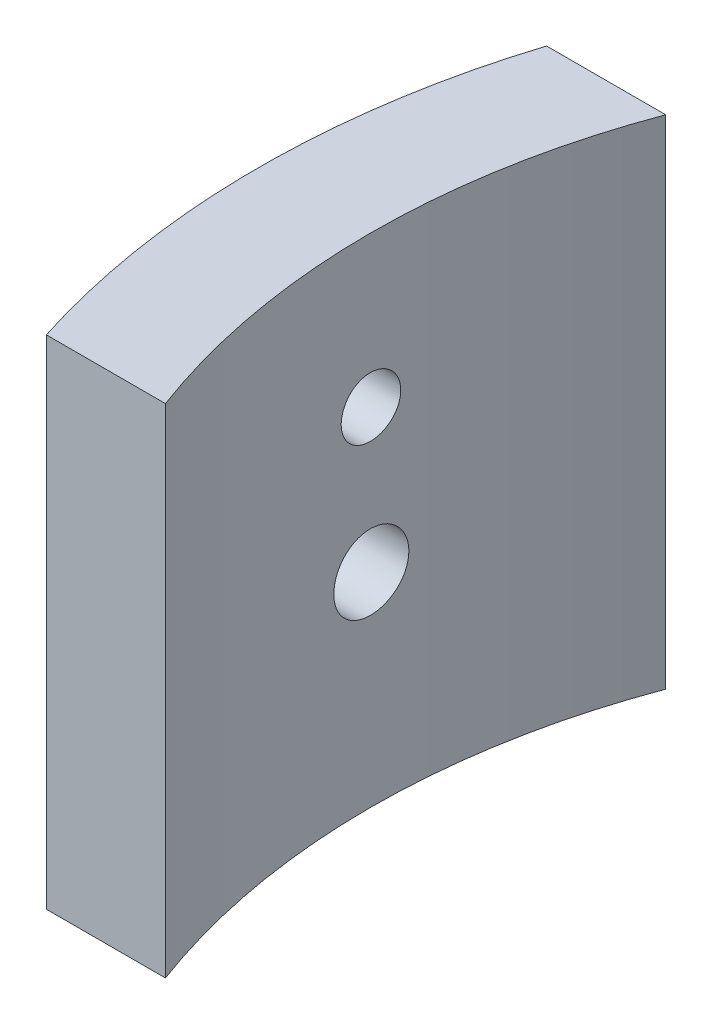
SolidWorks part; units mm, degrees
material "ABS"
ref_plane "Front Plane" through (0, 0, 0) normal (0, 0, 1) x (1, 0, 0)
ref_plane "Top Plane" through (0, 0, 0) normal (0, 1, 0) x (1, 0, 0)
ref_plane "Right Plane" through (0, 0, 0) normal (1, 0, 0) x (0, 0, -1)
sketch "Sketch1" plane through (0, 0, 0) normal (0, 1, 0) x (1, 0, 0)
  line L0 (-42.0402, -13.335) -> (-35.6902, -13.335)
  line L1 (-42.0402, 13.335) -> (-35.6902, 13.335)
  line L2 (-35.6902, 13.335) -> (0, 0) construction
  line L3 (0, 0) -> (-35.6902, -13.335) construction
  line L4 (-88.519, 13.335) -> (-35.6902, 13.335) construction
  arc A0 (-35.6902, 13.335) -> (-35.6902, -13.335) centre (0, 0) ccw
  arc A1 (-42.0402, 13.335) -> (-42.0402, -13.335) centre (0, 0) ccw
  dimension "D1" = 38.1
  dimension "D2" = 6.35
extrude "Boss-Extrude1" add sketch "Sketch1" along normal blind 38.1
ref_plane "Plane1" through (-42.0402, 0, 0) normal (-1, 0, 0) x (0, 0, 1)
sketch "Sketch2" plane through (-42.0402, 0, 0) normal (-1, 0, 0) x (0, 0, 1)
  line L0 (0, 38.1) -> (0, 0) construction
  line L1 (13.335, 38.1) -> (-13.335, 38.1) construction
  circle A0 centre (0, 30.0704) radius 1.5875
  circle A1 centre (0, 30.0704) radius 4.7625
  circle A2 centre (0, 30.0704) radius 1.5875 construction
  dimension "D1" = 3.175
extrude "Boss-Extrude3" add sketch "Sketch2" along normal up to surface (2.4098 mm away)
ref_plane "Plane2" through (-44.1044, 0, 0) normal (-1, 0, 0) x (0, 0, 1)
ref_plane "Plane3" through (-50.4544, 0, 0) normal (-1, 0, 0) x (0, 0, 1)
sketch "Sketch3" plane through (0, 0, 0) normal (0, -1, 0) x (1, 0, 0)
  line L0 (-42.0402, 13.335) -> (-35.6902, 13.335)
  line L1 (-42.0402, -13.335) -> (-35.6902, -13.335)
  arc A0 (-42.0402, 13.335) -> (-42.0402, -13.335) centre (0, 0) ccw
  arc A1 (-35.6902, -13.335) -> (-35.6902, 13.335) centre (0, 0) cw
  arc A2 (-42.0402, 13.335) -> (-42.0402, -13.335) centre (0, 0) ccw construction
  arc A3 (-35.6902, 13.335) -> (-35.6902, -13.335) centre (0, 0) ccw construction
extrude "Cut-Extrude1" cut sketch "Sketch3" against normal up to surface (11.5792 mm away)
sketch "Sketch5" plane through (-44.45, 0, 0) normal (-1, 0, 0) x (0, 0, 1)
  circle A0 centre (0, 30.0704) radius 1.5875
  circle A1 centre (0, 30.0704) radius 1.5875 construction
extrude "Cut-Extrude4" cut sketch "Sketch5" against normal through all
ref_plane "Plane4" through (-35.6902, 0, 0) normal (1, 0, 0) x (0, 0, -1)
sketch "Sketch6" plane through (-35.6902, 0, 0) normal (1, 0, 0) x (0, 0, -1)
  circle A0 centre (0, 22.4504) radius 2
  dimension "D1" = 4
extrude "Cut-Extrude5" cut sketch "Sketch6" against normal up to surface (8.3689 mm away)
